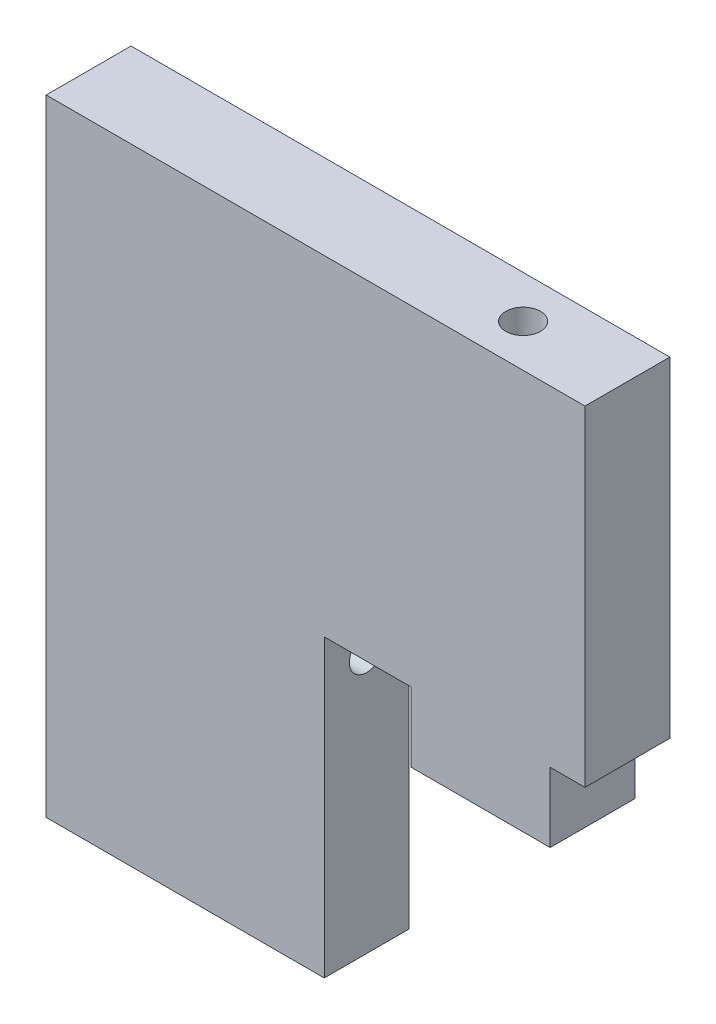
SolidWorks part; units mm, degrees
ref_plane "Front Plane" through (0, 0, 0) normal (0, 0, 1) x (1, 0, 0)
ref_plane "Top Plane" through (0, 0, 0) normal (0, 1, 0) x (1, 0, 0)
ref_plane "Right Plane" through (0, 0, 0) normal (1, 0, 0) x (0, 0, -1)
sketch "Sketch1" plane through (0, 0, 0) normal (0, 1, 0) x (1, 0, 0)
  circle A0 centre (0, 0) radius 76.2
  circle A1 centre (0, 0) radius 12.7
  dimension "D1" = 152.4
  dimension "D2" = 25.4
sketch "Sketch5" plane through (0, 0, 0) normal (0, 0, 1) x (1, 0, 0)
  line L1 (76.2, 266.7) -> (-317.5, 266.7)
  line L2 (76.2, 266.7) -> (76.2, 25.4)
  line L3 (76.2, 25.4) -> (50.8, 25.4)
  line L4 (-50.8, 25.4) -> (-114.3, 25.4)
  line L7 (-317.5, 266.7) -> (-317.5, -190.5)
  line L8 (-317.5, -190.5) -> (-114.3, -190.5)
  line L9 (-114.3, 25.4) -> (-114.3, -190.5)
  line L10 (50.8, 25.4) -> (50.8, -25.4)
  line L11 (50.8, -25.4) -> (-50.8, -25.4)
  line L12 (-50.8, 25.4) -> (-50.8, -25.4)
  point P1 (-215.9, -190.5)
  dimension "D1" = 457.2
  dimension "D2" = 203.2
  dimension "D3" = 393.7
  dimension "D4" = 215.9
  dimension "D5" = 317.5
  dimension "D6" = 190.5
  dimension "D7" = 50.8
  dimension "D8" = 50.8
  dimension "D9" = 165.1
extrude "Boss-Extrude3" add sketch "Sketch5" along normal mid plane 62
sketch "Sketch2" plane through (-317.5, 0, -457.2) normal (1, 0, 0) x (0, 0, -1)
  circle A0 centre (-457.2, 0) radius 12.7
  dimension "D1" = 25.4
extrude "Cut-Extrude1" cut sketch "Sketch2" along normal up to surface (317.5 mm away)
sketch "Sketch3" plane through (-317.5, 0, -457.2) normal (1, 0, 0) x (0, 0, -1)
  circle A0 centre (-457.2, 0) radius 19.05
  dimension "D1" = 38.1
sketch "Sketch6" plane through (0, 0, 0) normal (0, 1, 0) x (1, 0, 0)
  circle A0 centre (0, 0) radius 76.2
  circle A1 centre (0, 0) radius 12.7
  dimension "D1" = 152.4
  dimension "D2" = 25.4
extrude "Cut-Extrude3" cut sketch "Sketch6" against normal through all both and the other way through all contours A1
extrude "Cut-Extrude4" cut sketch "Sketch3" along normal blind 15.24
sketch "Sketch7" plane through (0, -190.5, 0) normal (0, -1, 0) x (1, 0, 0)
  line L0 (-317.5, 21.825) -> (-114.3, 21.825) construction
  line L1 (-317.5, 31) -> (-317.5, -31) construction
  line L2 (-317.5, -21.825) -> (-114.3, -21.825) construction
  line L3 (-114.3, 31) -> (-114.3, -31) construction
  line L5 (-317.5, 31) -> (-317.5, 21.825) construction
  line L6 (-317.5, 31) -> (-114.3, 31) construction
  line L7 (-317.5, -21.825) -> (-317.5, -31) construction
  line L8 (-317.5, -31) -> (-114.3, -31) construction
  circle A0 centre (-291.3042, 21.825) radius 5
  circle A1 centre (-291.3042, -21.825) radius 5
  circle A2 centre (-241.3042, 21.825) radius 5
  circle A3 centre (-241.3042, -21.825) radius 5
  circle A4 centre (-191.3042, 21.825) radius 5
  circle A5 centre (-191.3042, -21.825) radius 5
  dimension "D2" = 50
  dimension "D3" = 50
  dimension "D4" = 10
  dimension "D1" = 43.65
extrude "Cut-Extrude5" cut sketch "Sketch7" against normal blind 25.4
